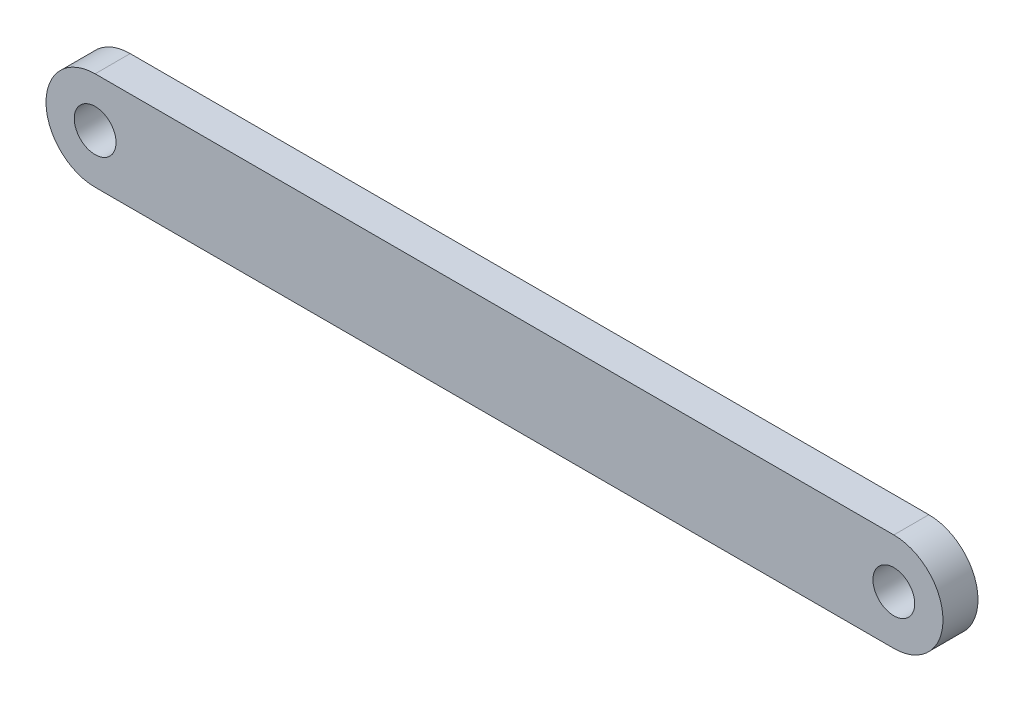
SolidWorks part; units mm, degrees
material "Pine"
ref_plane "Front" through (0, 0, 0) normal (0, 0, 1) x (1, 0, 0)
ref_plane "Top" through (0, 0, 0) normal (0, 1, 0) x (1, 0, 0)
ref_plane "Right" through (0, 0, 0) normal (1, 0, 0) x (0, 0, -1)
sketch "Sketch1" plane through (0, 0, 0) normal (0, 0, 1) x (1, 0, 0)
  line L1 (-50, 4) -> (50, 4)
  line L2 (-50, 4) -> (-50, -4)
  line L3 (-50, -4) -> (50, -4)
  line L4 (50, 4) -> (50, -4)
  line L5 (-50, 4) -> (50, -4) construction
  line L6 (-50, -4) -> (50, 4) construction
  point P0 (0, 0)
  dimension "D1" = 100
  dimension "D2" = 8
extrude "Boss-Extrude1" add sketch "Sketch1" along normal blind 2.85
sketch "Sketch2" plane through (0, 0, 2.85) normal (0, 0, 1) x (1, 0, 0)
  line L0 (46, -4) -> (51, -4)
  line L1 (51, -4) -> (51, 4)
  line L2 (51, 4) -> (46, 4)
  line L3 (50, -4) -> (50, 4) construction
  line L4 (50, 4) -> (-50, 4) construction
  line L5 (-50, -4) -> (50, -4) construction
  arc A0 (46, -4) -> (46, 4) centre (46, 0) ccw
  dimension "D1" = 1
extrude "Cut-Extrude1" cut sketch "Sketch2" against normal through all
sketch "Sketch3" plane through (0, 0, 2.85) normal (0, 0, 1) x (1, 0, 0)
  circle A0 centre (46, 0) radius 1.7
  dimension "D1" = 3.4
extrude "Cut-Extrude2" cut sketch "Sketch3" against normal through all
mirror "Mirror1" about plane through (0, 0, 0) normal (1, 0, 0) of "Cut-Extrude2", "Cut-Extrude1"
sketch "Sketch4" plane through (0, 0, 2.85) normal (0, 0, 1) x (1, 0, 0)
  line L0 (-19, 0) -> (0, 0) construction
  circle A0 centre (-19, 0) radius 1.7
  circle A1 centre (-46, 0) radius 1.7 construction
  dimension "D1" = 3.4
  dimension "D2" = 27
extrude "Cut-Extrude3" cut sketch "Sketch4" against normal through all
sketch "Sketch5" plane through (0, 0, 2.85) normal (0, 0, 1) x (1, 0, 0)
  line L0 (-19, 4) -> (-50, 4)
  line L1 (-50, 4) -> (-50, -4)
  line L2 (-50, -4) -> (-19, -4)
  line L3 (46, 4) -> (-46, 4) construction
  arc A0 (-19, 4) -> (-19, -4) centre (-19, 0) ccw
  arc A1 (-46, 4) -> (-46, -4) centre (-46, 0) ccw construction
extrude "Cut-Extrude4" cut sketch "Sketch5" against normal through all
